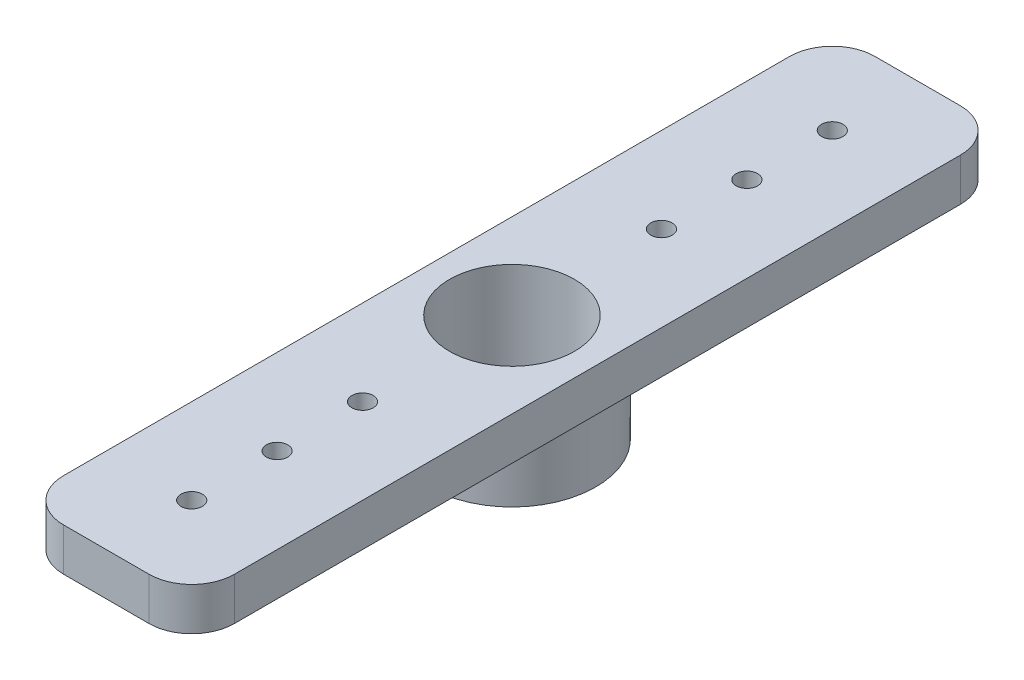
SolidWorks part; units mm, degrees
material "ABS PC"
ref_plane "Front Plane" through (0, 0, 0) normal (0, 0, 1) x (1, 0, 0)
ref_plane "Top Plane" through (0, 0, 0) normal (0, 1, 0) x (1, 0, 0)
ref_plane "Right Plane" through (0, 0, 0) normal (1, 0, 0) x (0, 0, -1)
sketch "Sketch1" plane through (0, 0, 0) normal (0, 1, 0) x (1, 0, 0)
  line L1 (0, 0) -> (8, 0)
  line L2 (0, 0) -> (0, 38)
  line L3 (0, 38) -> (8, 38)
  line L4 (8, 0) -> (8, 38)
  dimension "D1" = 38
  dimension "D2" = 8
extrude "Boss-Extrude1" add sketch "Sketch1" along normal blind 2
sketch "Sketch2" plane through (0, 0, 0) normal (0, -1, 0) x (1, 0, 0)
  line L0 (0, 0) -> (8, 0) construction
  line L1 (0, -38) -> (0, 0) construction
  circle A0 centre (4, -19) radius 2.925
  circle A1 centre (4, -19) radius 3.925
  point P0 (4, 0)
  point P1 (0, -19)
  point P4 (4, -19)
  dimension "D1" = 5.85
  dimension "D3" = 7.85
  dimension "D2" = 1
extrude "Boss-Extrude2" add sketch "Sketch2" along normal blind 3
sketch "Sketch3" plane through (0, 0, 0) normal (0, -1, 0) x (1, 0, 0)
  line L0 (0, 0) -> (8, 0) construction
  line L1 (4, -19) -> (15.8388, -19) construction
  line L2 (15.8388, -19) -> (-7.9376, -19) construction
  circle A0 centre (4, -19) radius 2.925
  circle A1 centre (4, -19) radius 3.925 construction
  circle A2 centre (4, -19) radius 3.925 construction
  circle A3 centre (4, -4) radius 0.5
  circle A4 centre (4, -8) radius 0.5
  circle A5 centre (4, -12) radius 0.5
  circle A6 centre (4, -26) radius 0.5
  circle A7 centre (4, -30) radius 0.5
  circle A8 centre (4, -34) radius 0.5
  point P3 (4, 0)
  point P4 (4, -4)
  point P7 (4, -8)
  point P8 (4, -12)
  point P9 (4, -15.075)
  dimension "D1" = 4
  dimension "D4" = 1
  dimension "D5" = 1
  dimension "D6" = 1
  dimension "D2" = 4
  dimension "D3" = 4
extrude "Cut-Extrude1" cut sketch "Sketch3" against normal blind 3
fillet "Fillet3" radius 2 4 edges at (8, 1, -38) (0, 1, -38) (0, 1, 0) (8, 1, 0)
